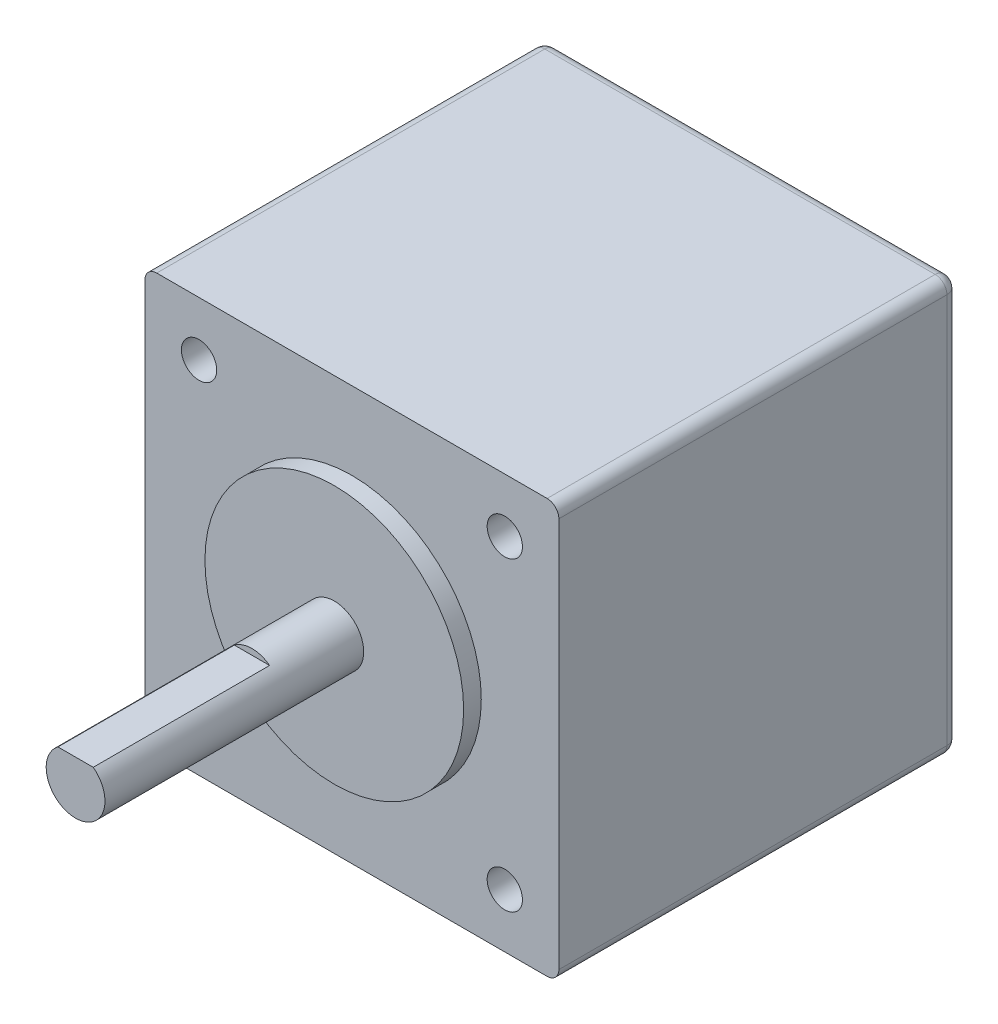
SolidWorks part; units mm, degrees
ref_plane "Front Plane" through (0, 0, 0) normal (0, 0, 1) x (1, 0, 0)
ref_plane "Top Plane" through (0, 0, 0) normal (0, 1, 0) x (1, 0, 0)
ref_plane "Right Plane" through (0, 0, 0) normal (1, 0, 0) x (0, 0, -1)
sketch "Sketch1" plane through (0, 0, 0) normal (0, 0, 1) x (1, 0, 0)
  line L1 (-17.6, -17.6) -> (17.6, -17.6)
  line L2 (-17.6, -17.6) -> (-17.6, 17.6)
  line L3 (-17.6, 17.6) -> (17.6, 17.6)
  line L4 (17.6, -17.6) -> (17.6, 17.6)
  line L5 (-17.6, -17.6) -> (17.6, 17.6) construction
  line L6 (-17.6, 17.6) -> (17.6, -17.6) construction
  point P0 (0, 0)
  dimension "D1" = 35.2
  dimension "D2" = 35.2
extrude "Boss-Extrude1" add sketch "Sketch1" along normal blind 34
sketch "Sketch2" plane through (0, 0, 34) normal (0, 0, 1) x (1, 0, 0)
  circle A0 centre (0, 0) radius 11
  dimension "D1" = 22
extrude "Boss-Extrude2" add sketch "Sketch2" along normal blind 1.5
sketch "Sketch3" plane through (0, 0, 35.5) normal (0, 0, 1) x (1, 0, 0)
  circle A0 centre (0, 0) radius 2.5
  dimension "D1" = 5
extrude "Boss-Extrude3" add sketch "Sketch3" along normal blind 22
sketch "Sketch4" plane through (0, 0, 0) normal (1, 0, 0) x (0, 0, -1)
  line L1 (-57.5, 2.5) -> (-42.5, 2.5)
  line L2 (-57.5, 2.5) -> (-57.5, 2)
  line L3 (-57.5, 2) -> (-42.5, 2)
  line L4 (-42.5, 2.5) -> (-42.5, 2)
  dimension "D1" = 15
  dimension "D2" = 0.5
extrude "Cut-Extrude1" cut sketch "Sketch4" against normal mid plane 10
sketch "Sketch5" plane through (0, 0, 34) normal (0, 0, 1) x (1, 0, 0)
  line L1 (-13, -13) -> (13, -13) construction
  line L2 (-13, -13) -> (-13, 13) construction
  line L3 (-13, 13) -> (13, 13) construction
  line L4 (13, -13) -> (13, 13) construction
  line L5 (-13, -13) -> (13, 13) construction
  line L6 (-13, 13) -> (13, -13) construction
  circle A0 centre (-13, 13) radius 1.5
  circle A1 centre (13, 13) radius 1.5
  circle A2 centre (13, -13) radius 1.5
  circle A3 centre (-13, -13) radius 1.5
  point P0 (0, 0)
  dimension "D3" = 3
  dimension "D1" = 26
  dimension "D2" = 26
  dimension "D4" = 4
extrude "Cut-Extrude2" cut sketch "Sketch5" against normal blind 4.5
fillet "Fillet1" radius 1 8 edges at (0, 17.6, 0) (-17.6, 0, 0) (0, -17.6, 0) (17.6, 0, 0) (-17.6, -17.6, 17) (17.6, -17.6, 17) (-17.6, 17.6, 17) (17.6, 17.6, 17)
